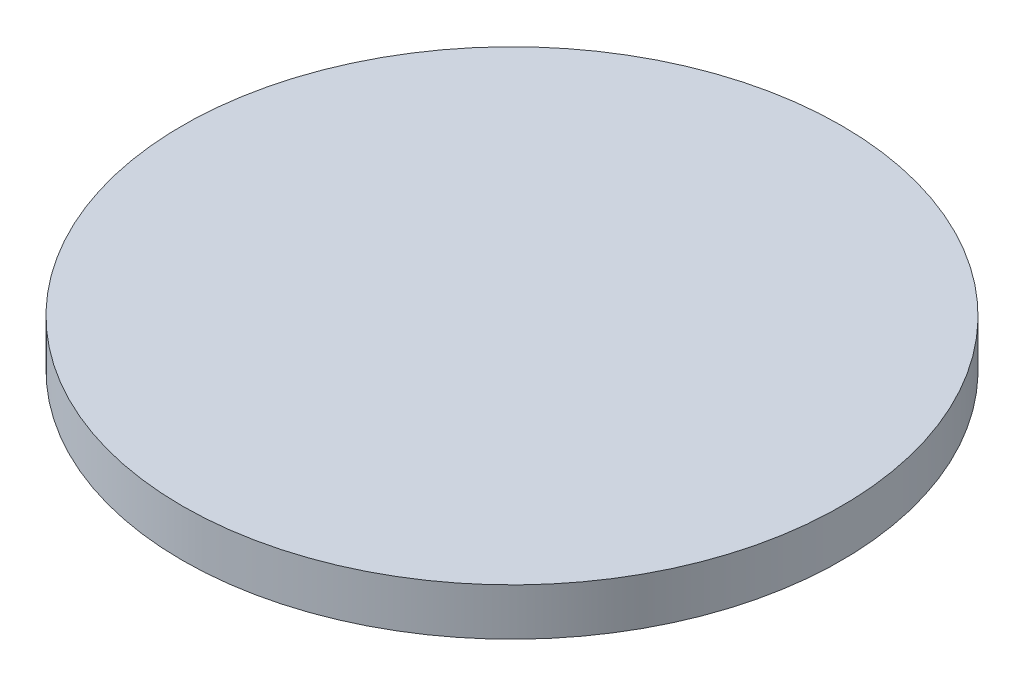
SolidWorks part; units mm, degrees
material "Polyurethane Foam Flexible"
ref_plane "Front Plane" through (0, 0, 0) normal (0, 0, 1) x (1, 0, 0)
ref_plane "Top Plane" through (0, 0, 0) normal (0, 1, 0) x (1, 0, 0)
ref_plane "Right Plane" through (0, 0, 0) normal (1, 0, 0) x (0, 0, -1)
sketch "Sketch1" plane through (0, 0, 0) normal (0, 1, 0) x (1, 0, 0)
  circle A0 centre (0, 0) radius 44.45
  dimension "D1" = 88.9
extrude "Boss-Extrude1" add sketch "Sketch1" along normal blind 6.35 contours A0
